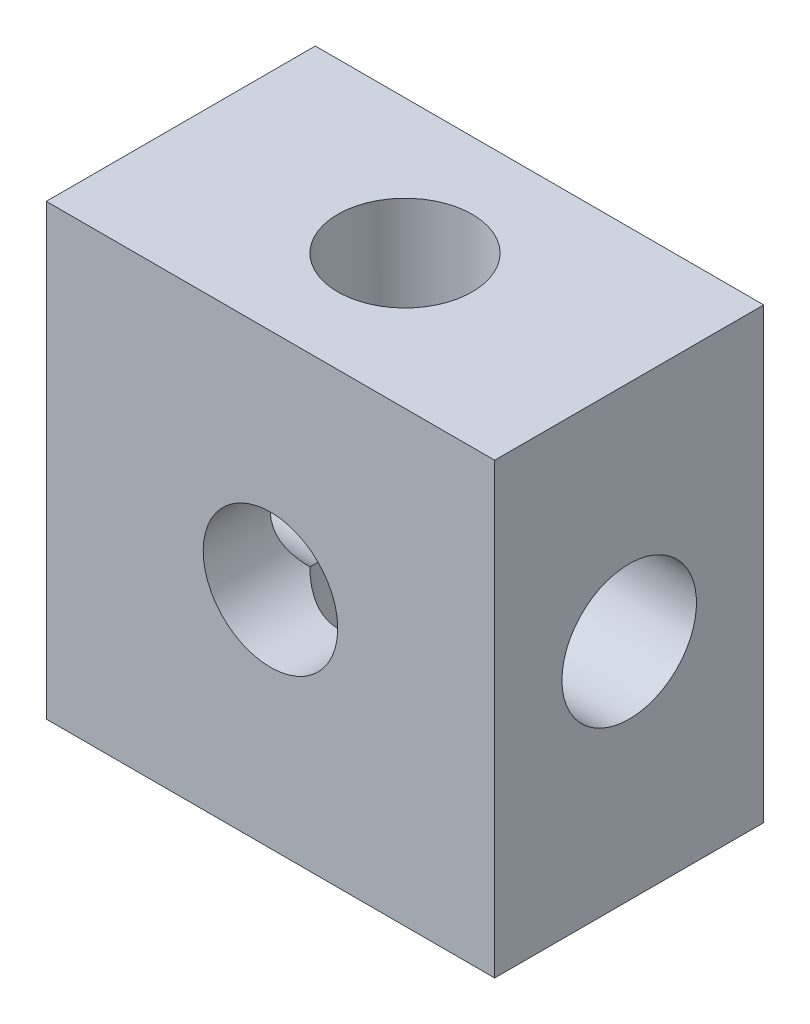
SolidWorks part; units mm, degrees
ref_plane "前视基准面" through (0, 0, 0) normal (0, 0, 1) x (1, 0, 0)
ref_plane "上视基准面" through (0, 0, 0) normal (0, 1, 0) x (1, 0, 0)
ref_plane "右视基准面" through (0, 0, 0) normal (1, 0, 0) x (0, 0, -1)
sketch "草图1" plane through (0, 0, 0) normal (0, 0, 1) x (1, 0, 0)
  line L0 (0, 0) -> (10, 0)
  line L1 (10, 0) -> (10, 10)
  line L2 (10, 10) -> (0, 10)
  line L3 (0, 10) -> (0, 0)
  dimension "D1" = 10
  dimension "D2" = 10
extrude "凸台-拉伸1" add sketch "草图1" along normal blind 6
sketch "草图2" plane through (0, 0, 0) normal (0, 0, -1) x (-1, 0, 0)
  circle A0 centre (-5, 5) radius 1.5
extrude "切除-拉伸1" cut sketch "草图2" against normal through all
sketch "草图3" plane through (0, 10, 0) normal (0, 1, 0) x (1, 0, 0)
  circle A0 centre (5, -3) radius 1.5
extrude "切除-拉伸2" cut sketch "草图3" against normal through all
sketch "草图4" plane through (0, 0, 0) normal (-1, 0, 0) x (0, 0, 1)
  circle A0 centre (3, 5) radius 1.5
extrude "切除-拉伸3" cut sketch "草图4" against normal through all
